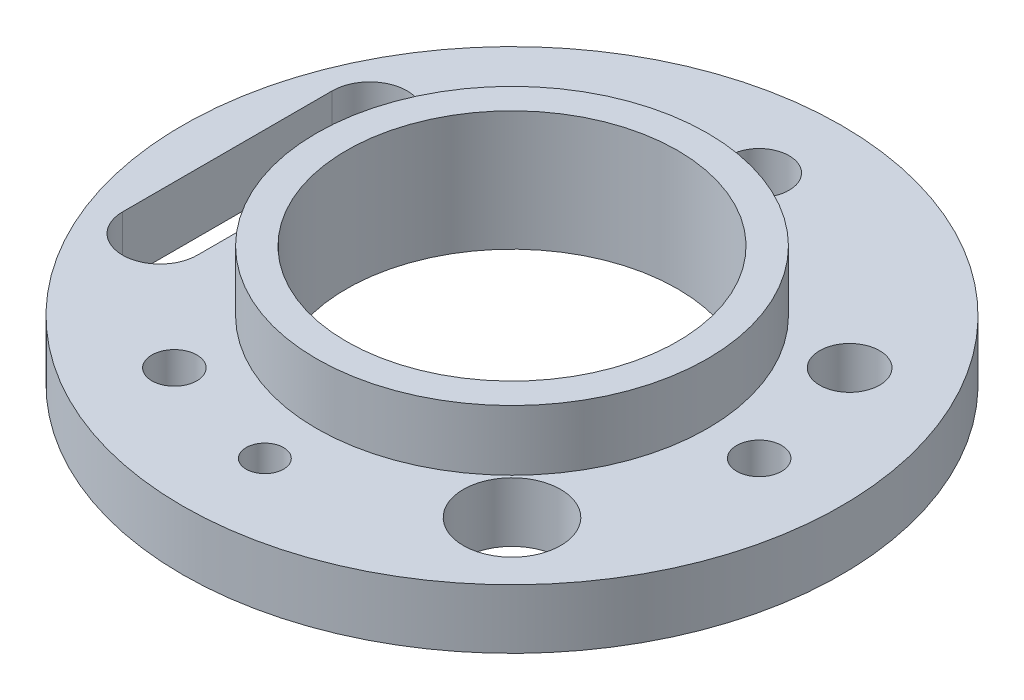
SolidWorks part; units mm, degrees
material "Brass"
ref_plane "Front Plane" through (0, 0, 0) normal (0, 0, 1) x (1, 0, 0)
ref_plane "Top Plane" through (0, 0, 0) normal (0, 1, 0) x (1, 0, 0)
ref_plane "Right Plane" through (0, 0, 0) normal (1, 0, 0) x (0, 0, -1)
sketch "Sketch1" plane through (0, 0, 0) normal (0, 0, 1) x (1, 0, 0)
  line L0 (0, 0) -> (0, 50.189) construction
  line L1 (11.05, 0) -> (11.05, 50.189) construction
  line L2 (11.05, 0) -> (11.05, 8)
  line L3 (11.05, 8) -> (13.05, 8)
  line L4 (13.05, 8) -> (13.05, 3.9693)
  line L5 (13.05, 3.9693) -> (22, 3.9693)
  line L6 (22, 3.9693) -> (22, 0)
  line L7 (22, 0) -> (11.05, 0)
  dimension "D1" = 11.05
  dimension "D2" = 8
  dimension "D3" = 22
revolve "Revolve1" add sketch "Sketch1" angle 360 about L0
sketch "Sketch3" plane through (0, 0, 0) normal (0, 1, 0) x (1, 0, 0)
  line L0 (0, 0) -> (29.292, 0) construction
  line L1 (0, 0) -> (-28.8006, 0) construction
  line L2 (-16.5, 0) -> (-16.5, 7) construction
  line L3 (-14, -7) -> (-14, 7)
  line L4 (-19, 7) -> (-19, -7)
  circle A0 centre (0, 0) radius 16.5 construction
  circle A1 centre (16.5, 0) radius 1.5
  circle A2 centre (-8.25, -14.2894) radius 1.5
  circle A3 centre (-8.25, 14.2894) radius 1.5
  arc A4 (-14, 7) -> (-19, 7) centre (-16.5, 7) ccw
  arc A5 (-14, -7) -> (-19, -7) centre (-16.5, -7) cw
  arc A6 (16.5, 0) -> (11.6673, -11.6673) centre (0, 0) cw construction
  circle A7 centre (11.6673, -11.6673) radius 3.25
  arc A8 (14.2894, 8.25) -> (16.5, 0) centre (0, 0) cw construction
  circle A9 centre (14.2894, 8.25) radius 2
  circle A10 centre (16.5, 0) radius 3.005 construction
  circle A11 centre (0, 16.5) radius 2
  circle A12 centre (0, -16.5) radius 1.25
  point P12 (0, 0)
  point P20 (-14, 0)
  point P22 (-19, 0)
  dimension "D1" = 3
  dimension "D2" = 2.5
extrude "Cut-Extrude1" cut sketch "Sketch3" along normal blind 10
